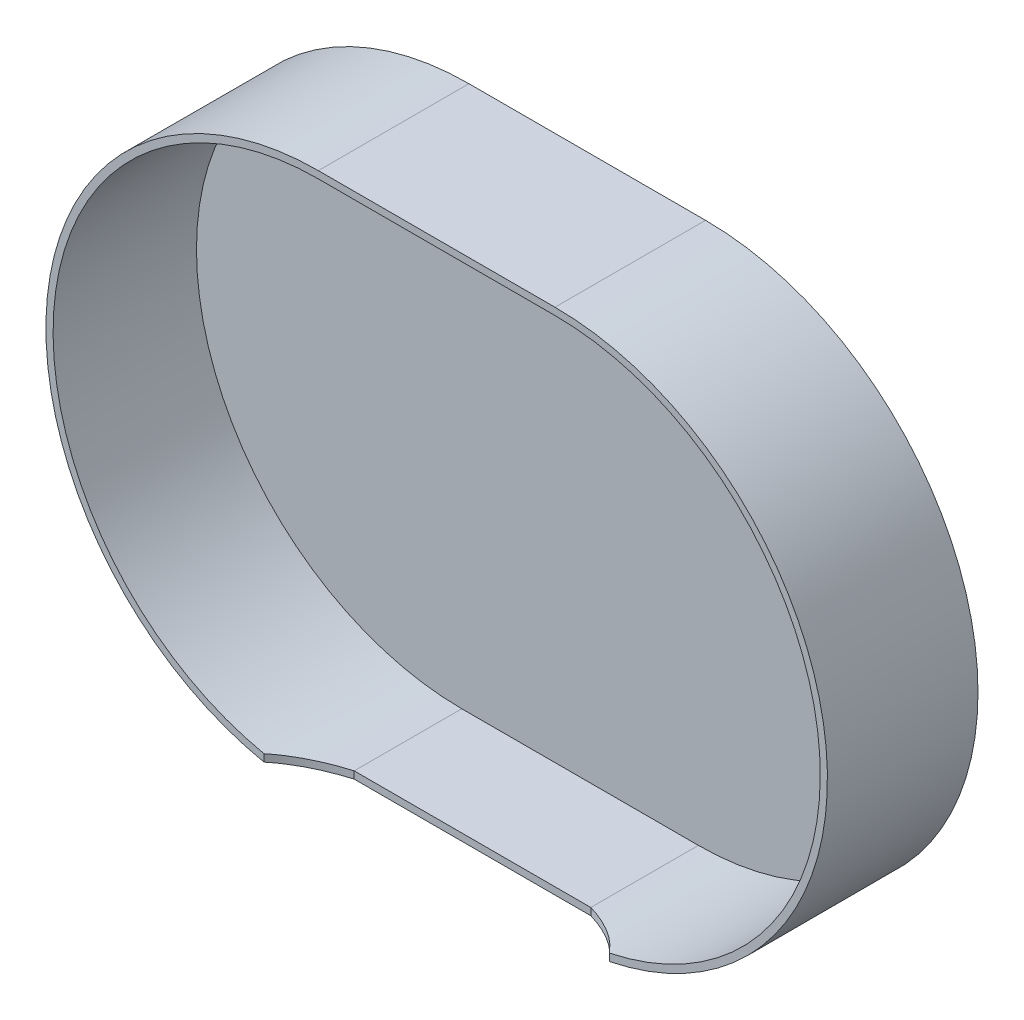
SolidWorks part; units mm, degrees
ref_plane "前视基准面" through (0, 0, 0) normal (0, 0, 1) x (1, 0, 0)
ref_plane "上视基准面" through (0, 0, 0) normal (0, 1, 0) x (1, 0, 0)
ref_plane "右视基准面" through (0, 0, 0) normal (1, 0, 0) x (0, 0, -1)
sketch "草图1" plane through (0, 0, 0) normal (0, 0, 1) x (1, 0, 0)
  line L1 (0, 38) -> (33, 38)
  line L3 (33, -38) -> (0, -38)
  arc A0 (0, 38) -> (0, -38) centre (0, 0) ccw
  arc A1 (33, -38) -> (33, 38) centre (33, 0) ccw
extrude "凸台-拉伸1" add sketch "草图1" along normal blind 1
sketch "草图2" plane through (0, 0, 1) normal (0, 0, 1) x (1, 0, 0)
  line L0 (0, 38) -> (33, 38)
  line L1 (0, 37) -> (33, 37)
  line L2 (0, -38) -> (33, -38)
  line L4 (33, -37) -> (0, -37)
  arc A0 (0, 38) -> (0, -38) centre (0, 0) ccw
  arc A1 (33, -38) -> (33, 38) centre (33, 0) ccw
  arc A2 (0, 37) -> (0, -37) centre (0, 0) ccw
  arc A3 (33, -37) -> (33, 37) centre (33, 0) ccw
extrude "凸台-拉伸2" add sketch "草图2" along normal blind 20
sketch "草图3" plane through (0, -38, 0) normal (0, -1, 0) x (1, 0, 0)
  line L1 (0, 21) -> (33, 21) construction
  line L2 (33, 16) -> (33, 21)
  line L3 (33, 21) -> (33, 0) construction
  line L4 (33, 16) -> (0, 16)
  line L5 (0, 21) -> (0, 0) construction
  line L6 (0, 16) -> (0, 21)
  line L7 (16.5, 21) -> (-7.5758, 21)
  line L8 (16.5, 21) -> (40.5758, 21)
  arc A1 (33, 16) -> (40.5758, 21) centre (28.5379, 31) ccw
  arc A2 (-7.5758, 21) -> (0, 16) centre (4.4621, 31) ccw
  line M4 (33, 0) -> (33, 21)
  line M5 (33, 21) -> (0, 21)
  line M6 (0, 21) -> (0, 0)
extrude "切除-拉伸1" cut sketch "草图3" against normal blind 20 contours L4 M4 M5 M6 | L7 A2 M6 | A1 L8 M4
